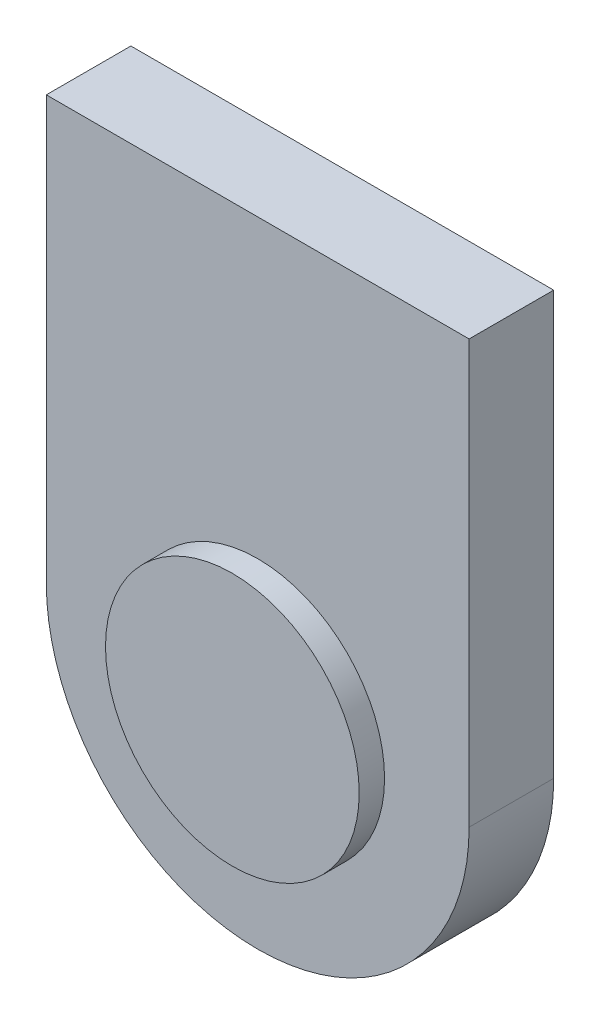
SolidWorks part; units mm, degrees
ref_plane "Front Plane" through (0, 0, 0) normal (0, 0, 1) x (1, 0, 0)
ref_plane "Top Plane" through (0, 0, 0) normal (0, 1, 0) x (1, 0, 0)
ref_plane "Right Plane" through (0, 0, 0) normal (1, 0, 0) x (0, 0, -1)
sketch "Sketch1" plane through (0, 0, 0) normal (0, 0, 1) x (1, 0, 0)
  line L0 (-25, 0) -> (-25, 50)
  line L1 (-25, 50) -> (25, 50)
  line L2 (25, 50) -> (25, 0)
  arc A1 (-25, 0) -> (25, 0) centre (0, 0) ccw
  dimension "D2" = 25
  dimension "D3" = 50
extrude "Boss-Extrude1" add sketch "Sketch1" along normal mid plane 10
sketch "Sketch2" plane through (0, 0, 0) normal (0, 0, 1) x (1, 0, 0)
  line L0 (0, 70.5172) -> (0, -165.5728) construction
  line L1 (-78.0593, 0) -> (83.3815, 0) construction
sketch "Sketch3" plane through (0, 0, 5) normal (0, 0, 1) x (1, 0, 0)
  circle A0 centre (0, 0) radius 15
  dimension "D1" = 30
extrude "Boss-Extrude2" add sketch "Sketch3" along normal blind 3
